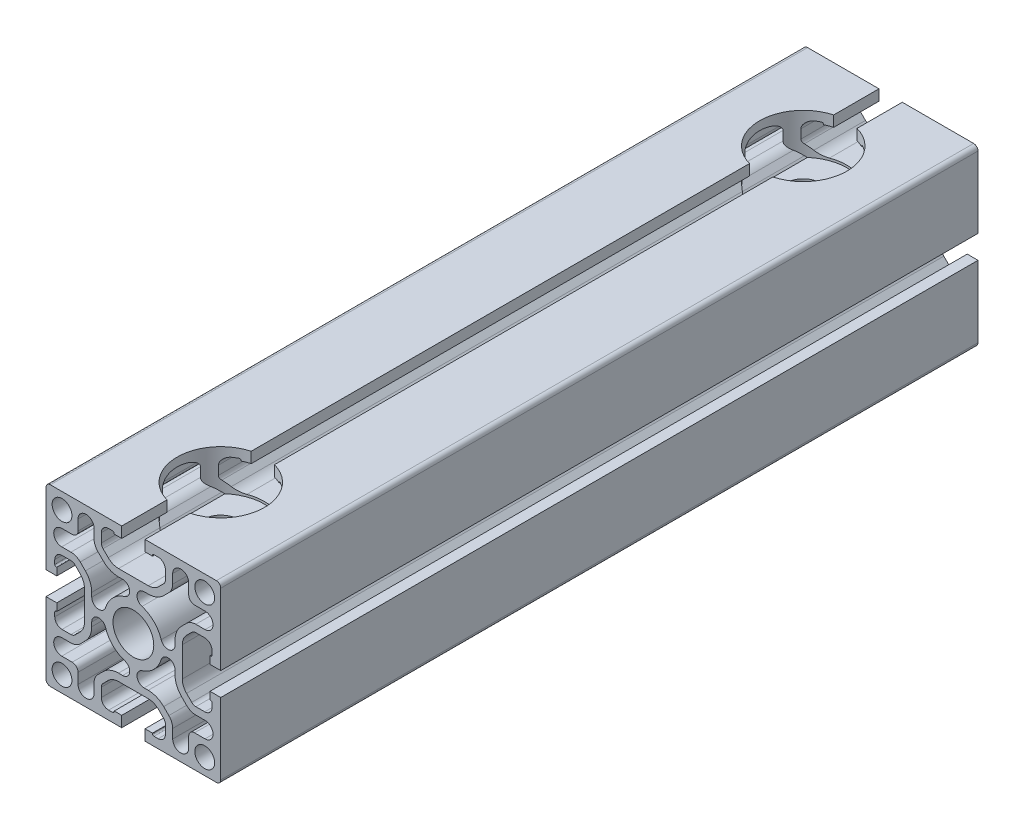
SolidWorks part; units mm, degrees
ref_plane "Płaszczyzna przednia" through (0, 0, 0) normal (0, 0, 1) x (1, 0, 0)
ref_plane "Płaszczyzna górna" through (0, 0, 0) normal (0, 1, 0) x (1, 0, 0)
ref_plane "Płaszczyzna prawa" through (0, 0, 0) normal (1, 0, 0) x (0, 0, -1)
ref_plane "Plane1" through (0, 0, 0) normal (0, 0, -1) x (-1, 0, 0)
sketch "Sketch1" plane through (0, 0, 0) normal (0, 0, -1) x (-1, 0, 0)
  line L0 (5.1034, -14.3) -> (3.6784, -14.3)
  line L1 (14.3, -3.6784) -> (14.3, -5.1134)
  line L2 (16.4818, -10.4017) -> (18.2431, -12.173)
  line L3 (21.434, -13.5) -> (24.6, -13.5)
  line L4 (24.6, -19) -> (21, -19)
  line L5 (19, -21) -> (19, -24.6)
  line L6 (13.5, -24.6) -> (13.5, -21.454)
  line L7 (12.182, -18.272) -> (10.4067, -16.4967)
  line L8 (-3.6784, -14.3) -> (-5.1034, -14.3)
  line L9 (-10.4067, -16.4967) -> (-12.182, -18.272)
  line L10 (-13.5, -21.454) -> (-13.5, -24.6)
  line L11 (-19, -24.6) -> (-19, -21)
  line L12 (-21, -19) -> (-24.6, -19)
  line L13 (-24.6, -13.5) -> (-21.434, -13.5)
  line L14 (-18.2431, -12.173) -> (-16.4818, -10.4017)
  line L15 (-14.3, -5.1134) -> (-14.3, -3.6784)
  line L16 (-5.1034, 14.3) -> (-3.6784, 14.3)
  line L17 (-14.3, 3.6784) -> (-14.3, 5.1134)
  line L18 (-16.4818, 10.4017) -> (-18.2431, 12.173)
  line L19 (-21.434, 13.5) -> (-24.6, 13.5)
  line L20 (-24.6, 19) -> (-21, 19)
  line L21 (-19, 21) -> (-19, 24.6)
  line L22 (-13.5, 24.6) -> (-13.5, 21.454)
  line L23 (-12.182, 18.272) -> (-10.4067, 16.4967)
  line L24 (3.6784, 14.3) -> (5.1034, 14.3)
  line L25 (10.4067, 16.4967) -> (12.182, 18.272)
  line L26 (13.5, 21.454) -> (13.5, 24.6)
  line L27 (19, 24.6) -> (19, 21)
  line L28 (21, 19) -> (24.6, 19)
  line L29 (24.6, 13.5) -> (21.434, 13.5)
  line L30 (18.2431, 12.173) -> (16.4818, 10.4017)
  line L31 (14.3, 5.1134) -> (14.3, 3.6784)
  line L32 (5.1, 16.8) -> (-5.11, 16.8)
  line L33 (-8.6455, 18.2645) -> (-10.42, 20.04)
  line L34 (-11, 21.45) -> (-11, 24.5)
  line L35 (-8.5, 27) -> (-7.07, 27)
  line L36 (-6.57, 26.5) -> (-6.57, 26.3)
  line L37 (-6.57, 26.3) -> (-4, 26.3)
  line L38 (-4, 26.3) -> (-4, 30)
  line L39 (-4, 30) -> (-28.5, 30)
  line L40 (-30, 28.5) -> (-30, 4)
  line L41 (-30, 4) -> (-26.3, 4)
  line L42 (-26.3, 4) -> (-26.3, 6.57)
  line L43 (-26.3, 6.57) -> (-26.5, 6.57)
  line L44 (-27, 7.07) -> (-27, 8.5)
  line L45 (-24.5, 11) -> (-21.45, 11)
  line L46 (-20.0358, 10.4142) -> (-18.27, 8.65)
  line L47 (-16.8, 5.11) -> (-16.8, -5.1)
  line L48 (-18.2645, -8.6355) -> (-20.04, -10.41)
  line L49 (-21.45, -11) -> (-24.5, -11)
  line L50 (-27, -8.5) -> (-27, -7.07)
  line L51 (-26.5, -6.57) -> (-26.3, -6.57)
  line L52 (-26.3, -6.57) -> (-26.3, -4)
  line L53 (-26.3, -4) -> (-30, -4)
  line L54 (-30, -4) -> (-30, -28.5)
  line L55 (-28.5, -30) -> (-4, -30)
  line L56 (-4, -30) -> (-4, -26.3)
  line L57 (-4, -26.3) -> (-6.57, -26.3)
  line L58 (-6.57, -26.3) -> (-6.57, -26.5)
  line L59 (-7.07, -27) -> (-8.5, -27)
  line L60 (-11, -24.5) -> (-11, -21.45)
  line L61 (-10.4142, -20.0358) -> (-8.65, -18.26)
  line L62 (-5.11, -16.8) -> (5.1, -16.8)
  line L63 (8.64, -18.26) -> (10.41, -20.03)
  line L64 (11, -21.45) -> (11, -24.5)
  line L65 (8.5, -27) -> (7.07, -27)
  line L66 (6.57, -26.5) -> (6.57, -26.3)
  line L67 (6.57, -26.3) -> (4, -26.3)
  line L68 (4, -26.3) -> (4, -30)
  line L69 (4, -30) -> (28.5, -30)
  line L70 (30, -28.5) -> (30, -4)
  line L71 (30, -4) -> (26.3, -4)
  line L72 (26.3, -4) -> (26.3, -6.57)
  line L73 (26.3, -6.57) -> (26.5, -6.57)
  line L74 (27, -7.07) -> (27, -8.5)
  line L75 (24.5, -11) -> (21.45, -11)
  line L76 (20.0358, -10.4142) -> (18.26, -8.64)
  line L77 (16.8, -5.1) -> (16.8, 5.11)
  line L78 (18.26, 8.65) -> (20.0358, 10.4142)
  line L79 (21.45, 11) -> (24.5, 11)
  line L80 (27, 8.5) -> (27, 7.07)
  line L81 (26.5, 6.57) -> (26.3, 6.57)
  line L82 (26.3, 6.57) -> (26.3, 4)
  line L83 (26.3, 4) -> (30, 4)
  line L84 (30, 4) -> (30, 28.5)
  line L85 (28.5, 30) -> (4, 30)
  line L86 (4, 30) -> (4, 26.3)
  line L87 (4, 26.3) -> (6.57, 26.3)
  line L88 (6.57, 26.3) -> (6.57, 26.5)
  line L89 (7.07, 27) -> (8.5, 27)
  line L90 (11, 24.5) -> (11, 21.45)
  line L91 (10.4142, 20.0358) -> (8.64, 18.27)
  circle A0 centre (-24.5, 24.5) radius 3.4
  circle A1 centre (24.5, 24.5) radius 3.4
  circle A2 centre (-24.5, -24.49) radius 3.4
  circle A3 centre (24.5, -24.49) radius 3.4
  circle A4 centre (0, 0) radius 7
  arc A5 (3.6784, -14.3) -> (2.9597, -9.552) centre (3.6784, -11.8716) cw
  arc A6 (2.9597, -9.552) -> (9.552, -2.9597) centre (0, 0) ccw
  arc A7 (9.552, -2.9597) -> (14.3, -3.6784) centre (11.8716, -3.6784) cw
  arc A8 (14.3, -5.1134) -> (16.4818, -10.4017) centre (21.8, -5.1134) ccw
  arc A9 (18.2431, -12.173) -> (21.434, -13.5) centre (21.434, -9) ccw
  arc A10 (24.6, -13.5) -> (24.6, -19) centre (24.6, -16.25) cw
  arc A11 (21, -19) -> (19, -21) centre (21, -21) ccw
  arc A12 (19, -24.6) -> (13.5, -24.6) centre (16.25, -24.6) cw
  arc A13 (13.5, -21.454) -> (12.182, -18.272) centre (9, -21.454) ccw
  arc A14 (10.4067, -16.4967) -> (5.1034, -14.3) centre (5.1034, -21.8) ccw
  arc A15 (-9.552, -2.9597) -> (-2.9597, -9.552) centre (0, 0) ccw
  arc A16 (-2.9597, -9.552) -> (-3.6784, -14.3) centre (-3.6784, -11.8716) cw
  arc A17 (-5.1034, -14.3) -> (-10.4067, -16.4967) centre (-5.1034, -21.8) ccw
  arc A18 (-12.182, -18.272) -> (-13.5, -21.454) centre (-9, -21.454) ccw
  arc A19 (-13.5, -24.6) -> (-19, -24.6) centre (-16.25, -24.6) cw
  arc A20 (-19, -21) -> (-21, -19) centre (-21, -21) ccw
  arc A21 (-24.6, -19) -> (-24.6, -13.5) centre (-24.6, -16.25) cw
  arc A22 (-21.434, -13.5) -> (-18.2431, -12.173) centre (-21.434, -9) ccw
  arc A23 (-16.4818, -10.4017) -> (-14.3, -5.1134) centre (-21.8, -5.1134) ccw
  arc A24 (-14.3, -3.6784) -> (-9.552, -2.9597) centre (-11.8716, -3.6784) cw
  arc A25 (-3.6784, 14.3) -> (-2.9597, 9.552) centre (-3.6784, 11.8716) cw
  arc A26 (-2.9597, 9.552) -> (-9.552, 2.9597) centre (0, 0) ccw
  arc A27 (-9.552, 2.9597) -> (-14.3, 3.6784) centre (-11.8716, 3.6784) cw
  arc A28 (-14.3, 5.1134) -> (-16.4818, 10.4017) centre (-21.8, 5.1134) ccw
  arc A29 (-18.2431, 12.173) -> (-21.434, 13.5) centre (-21.434, 9) ccw
  arc A30 (-24.6, 13.5) -> (-24.6, 19) centre (-24.6, 16.25) cw
  arc A31 (-21, 19) -> (-19, 21) centre (-21, 21) ccw
  arc A32 (-19, 24.6) -> (-13.5, 24.6) centre (-16.25, 24.6) cw
  arc A33 (-13.5, 21.454) -> (-12.182, 18.272) centre (-9, 21.454) ccw
  arc A34 (-10.4067, 16.4967) -> (-5.1034, 14.3) centre (-5.1034, 21.8) ccw
  arc A35 (9.552, 2.9597) -> (2.9597, 9.552) centre (0, 0) ccw
  arc A36 (2.9597, 9.552) -> (3.6784, 14.3) centre (3.6784, 11.8716) cw
  arc A37 (5.1034, 14.3) -> (10.4067, 16.4967) centre (5.1034, 21.8) ccw
  arc A38 (12.182, 18.272) -> (13.5, 21.454) centre (9, 21.454) ccw
  arc A39 (13.5, 24.6) -> (19, 24.6) centre (16.25, 24.6) cw
  arc A40 (19, 21) -> (21, 19) centre (21, 21) ccw
  arc A41 (24.6, 19) -> (24.6, 13.5) centre (24.6, 16.25) cw
  arc A42 (21.434, 13.5) -> (18.2431, 12.173) centre (21.434, 9) ccw
  arc A43 (16.4818, 10.4017) -> (14.3, 5.1134) centre (21.8, 5.1134) ccw
  arc A44 (14.3, 3.6784) -> (9.552, 2.9597) centre (11.8716, 3.6784) cw
  arc A45 (-5.11, 16.8) -> (-8.6455, 18.2645) centre (-5.11, 21.8) cw
  arc A46 (-10.42, 20.04) -> (-11, 21.45) centre (-8.9925, 21.4515) cw
  arc A47 (-11, 24.5) -> (-8.5, 27) centre (-8.5, 24.5) cw
  arc A48 (-7.07, 27) -> (-6.57, 26.5) centre (-7.07, 26.5) cw
  arc A49 (-28.5, 30) -> (-30, 28.5) centre (-28.5, 28.5) ccw
  arc A50 (-26.5, 6.57) -> (-27, 7.07) centre (-26.5, 7.07) cw
  arc A51 (-27, 8.5) -> (-24.5, 11) centre (-24.5, 8.5) cw
  arc A52 (-21.45, 11) -> (-20.0358, 10.4142) centre (-21.45, 9) cw
  arc A53 (-18.27, 8.65) -> (-16.8, 5.11) centre (-21.7951, 5.111) cw
  arc A54 (-16.8, -5.1) -> (-18.2645, -8.6355) centre (-21.8, -5.1) cw
  arc A55 (-20.04, -10.41) -> (-21.45, -11) centre (-21.4424, -9.0384) cw
  arc A56 (-24.5, -11) -> (-27, -8.5) centre (-24.5, -8.5) cw
  arc A57 (-27, -7.07) -> (-26.5, -6.57) centre (-26.5, -7.07) cw
  arc A58 (-30, -28.5) -> (-28.5, -30) centre (-28.5, -28.5) ccw
  arc A59 (-6.57, -26.5) -> (-7.07, -27) centre (-7.07, -26.5) cw
  arc A60 (-8.5, -27) -> (-11, -24.5) centre (-8.5, -24.5) cw
  arc A61 (-11, -21.45) -> (-10.4142, -20.0358) centre (-9, -21.45) cw
  arc A62 (-8.65, -18.26) -> (-5.11, -16.8) centre (-5.1017, -21.8418) cw
  arc A63 (5.1, -16.8) -> (8.64, -18.26) centre (5.0917, -21.8418) cw
  arc A64 (10.41, -20.03) -> (11, -21.45) centre (8.9927, -21.4515) cw
  arc A65 (11, -24.5) -> (8.5, -27) centre (8.5, -24.5) cw
  arc A66 (7.07, -27) -> (6.57, -26.5) centre (7.07, -26.5) cw
  arc A67 (28.5, -30) -> (30, -28.5) centre (28.5, -28.5) ccw
  arc A68 (26.5, -6.57) -> (27, -7.07) centre (26.5, -7.07) cw
  arc A69 (27, -8.5) -> (24.5, -11) centre (24.5, -8.5) cw
  arc A70 (21.45, -11) -> (20.0358, -10.4142) centre (21.45, -9) cw
  arc A71 (18.26, -8.64) -> (16.8, -5.1) centre (21.8418, -5.0917) cw
  arc A72 (16.8, 5.11) -> (18.26, 8.65) centre (21.8418, 5.1017) cw
  arc A73 (20.0358, 10.4142) -> (21.45, 11) centre (21.45, 9) cw
  arc A74 (24.5, 11) -> (27, 8.5) centre (24.5, 8.5) cw
  arc A75 (27, 7.07) -> (26.5, 6.57) centre (26.5, 7.07) cw
  arc A76 (30, 28.5) -> (28.5, 30) centre (28.5, 28.5) ccw
  arc A77 (6.57, 26.5) -> (7.07, 27) centre (7.0699, 26.5001) cw
  arc A78 (8.5, 27) -> (11, 24.5) centre (8.5, 24.5) cw
  arc A79 (11, 21.45) -> (10.4142, 20.0358) centre (9, 21.45) cw
  arc A80 (8.64, 18.27) -> (5.1, 16.8) centre (5.101, 21.7951) cw
extrude "Boss-Extrude1" add sketch "Sketch1" against normal blind 260
sketch "Sketch2" plane through (0, 0, 0) normal (0, 1, 0) x (1, 0, 0)
  line L0 (30, -260) -> (30, 0) construction
  line L1 (4, -260) -> (28.5, -260) construction
  line L2 (-28.5, 0) -> (-4, 0) construction
  circle A0 centre (0.005, -230) radius 6
  circle A1 centre (0, -30) radius 6
  dimension "D3" = 12
  dimension "D1" = 29.995
  dimension "D2" = 30
  dimension "D4" = 30
  dimension "D5" = 30
extrude "Cut-Extrude1" cut sketch "Sketch2" against normal through all both and the other way through all
sketch "Sketch3" plane through (0, 0, 0) normal (0, 1, 0) x (1, 0, 0)
  circle A0 centre (0.005, -230) radius 15
  circle A1 centre (0, -30) radius 15
  dimension "D1" = 30
  dimension "D2" = 30
extrude "Cut-Extrude2" cut sketch "Sketch3" against normal blind 14 from surface at 30 starting at face at (-10.6244, 30, 130)
